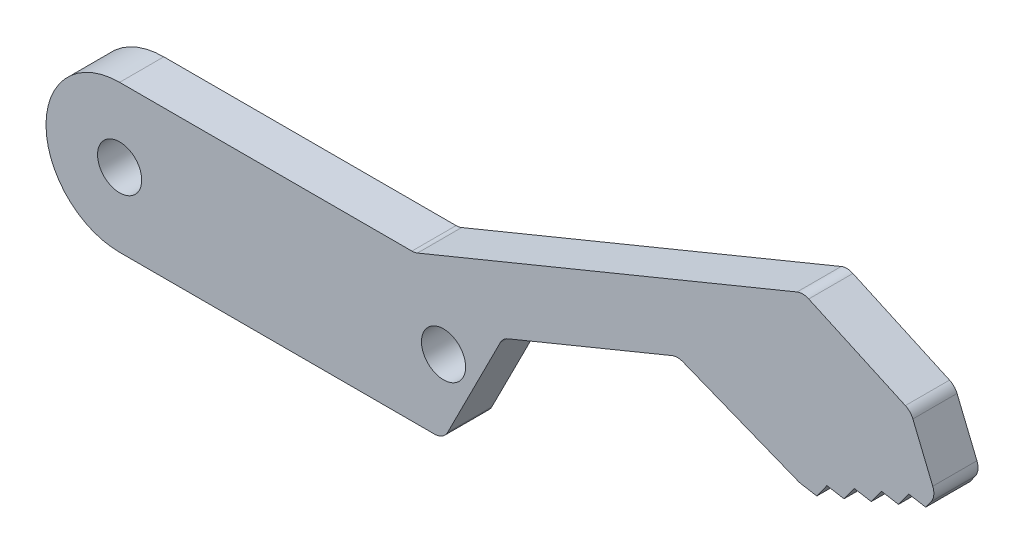
SolidWorks part; units mm, degrees
material "ABS"
ref_plane "Спереди" through (0, 0, 0) normal (0, 0, 1) x (1, 0, 0)
ref_plane "Сверху" through (0, 0, 0) normal (0, 1, 0) x (1, 0, 0)
ref_plane "Справа" through (0, 0, 0) normal (1, 0, 0) x (0, 0, -1)
sketch "Эскиз1" plane through (0, 0, 0) normal (0, 0, 1) x (1, 0, 0)
  line L0 (0, 0) -> (22, 0) construction
  line L1 (0, 5) -> (22, 5)
  line L2 (0, -5) -> (22, -5)
  line L3 (20.05, 5) -> (23.9914, -4.5863) construction
  line L4 (20.05, 5) -> (51.4959, 17.929) construction
  line L5 (23.9914, -4.5863) -> (55.4373, 8.3426) construction
  line L6 (51.4959, 17.929) -> (55.4373, 8.3426) construction
  line L7 (20.05, 5) -> (46.409, 15.8375)
  line L8 (46.409, 15.8375) -> (53.7261, 12.5046)
  line L9 (53.7261, 12.5046) -> (55.4373, 8.3426)
  line L10 (55.4373, 8.3426) -> (46.1885, 4.54)
  line L11 (46.1885, 4.54) -> (37.8854, 7.8358)
  line L12 (37.8854, 7.8358) -> (26.0289, 2.961)
  line L13 (46.1885, 4.54) -> (47.351, 4.3422)
  line L14 (47.351, 4.3422) -> (48.0382, 5.3005)
  line L15 (47.351, 4.3422) -> (54.7501, 7.3843) construction
  line L16 (48.0382, 5.3005) -> (49.2008, 5.1027)
  line L17 (49.2008, 5.1027) -> (49.888, 6.0611)
  line L18 (49.888, 6.0611) -> (51.0505, 5.8633)
  line L19 (51.0505, 5.8633) -> (51.7378, 6.8216)
  line L20 (51.7378, 6.8216) -> (52.9003, 6.6238)
  line L21 (52.9003, 6.6238) -> (53.5875, 7.5821)
  line L22 (53.5875, 7.5821) -> (54.7501, 7.3843)
  line L23 (54.7501, 7.3843) -> (55.4373, 8.3426)
  line L24 (26.0289, 2.961) -> (22, -5)
  arc A0 (0, 5) -> (0, -5) centre (0, 0) ccw
  arc A1 (22, -5) -> (22, 5) centre (22, 0) ccw
  circle A2 centre (0, 0) radius 1.5
  circle A3 centre (22, 0) radius 1.5
  point P3 (11, 0)
  dimension "D11" = 3
  dimension "D1" = 10
  dimension "D2" = 22
  dimension "D3" = 157.65
  dimension "D4" = 1.95
  dimension "D5" = 34
  dimension "D6" = 12.8195
  dimension "D7" = 10
  dimension "D8" = 4.5
  dimension "D9" = 5.5
  dimension "D10" = 136
  dimension "D12" = 2
  dimension "D13" = 0.625
  dimension "D14" = 8
extrude "Бобышка-Вытянуть2" add sketch "Эскиз1" against normal blind 3 contours L13 L14 L10 | L16 L17 L10 | L18 L19 L10 | L20 L21 L10 | L22 L23 L10 | A1 L12 L11 L10 L9 L8 L7 L1 | A1 L1 A0 L2 A3 A2
fillet "Скругление1" radius 1 8 edges at (46.1885, 4.54, -1.5) (55.4373, 8.3426, -1.5) (53.7261, 12.5046, -1.5) (46.409, 15.8375, -1.5) (20.05, 5, -1.5) (37.8854, 7.8358, -1.5) (26.0289, 2.961, -1.5) (22, -5, -1.5)
scale "Масштаб1" scale about centroid uniform scaling yes scale factor 2.2
equation "\"Scale\"= 1"
equation "\"D1@Эскиз1\"=10*\"Scale\""
equation "\"D2@Эскиз1\"=22*\"Scale\""
equation "\"D4@Эскиз1\"=1.95*\"Scale\""
equation "\"D5@Эскиз1\"=34*\"Scale\""
equation "\"D9@Эскиз1\"=5.5*\"Scale\""
equation "\"D6@Эскиз1\"=12.8195098*\"Scale\""
equation "\"D8@Эскиз1\"=4.50*\"Scale\""
equation "\"D14@Эскиз1\"=8.00мм*\"Scale\""
equation "\"D7@Эскиз1\"=10.00мм*\"Scale\""
equation "\"D12@Эскиз1\"=2.00мм*\"Scale\""
equation "\"D1@Скругление1\"=1.00мм*\"Scale\""
